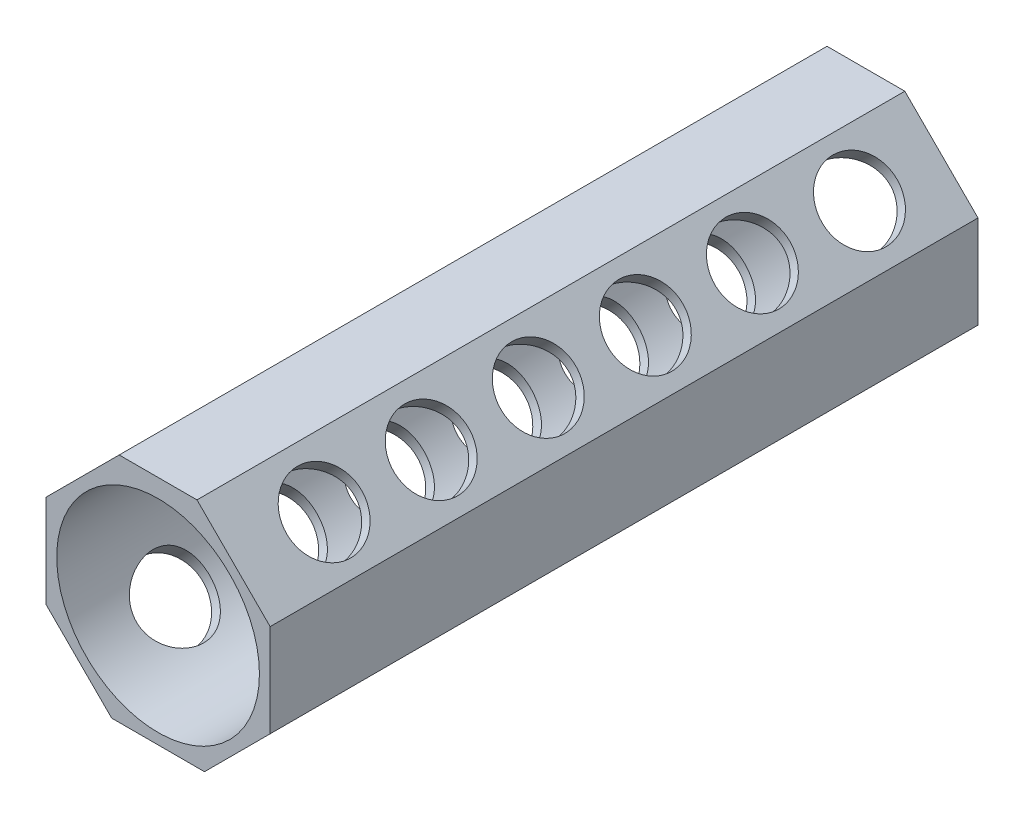
SolidWorks part; units mm, degrees
ref_plane "Ebene vorne" through (0, 0, 0) normal (1, 0, 0) x (0, 1, 0)
ref_plane "Ebene oben" through (0, 0, 0) normal (0, 0, 1) x (0, 1, 0)
ref_plane "Ebene rechts" through (0, 0, 0) normal (0, 1, 0) x (-1, 0, 0)
sketch "Skizze1" plane through (0, 0, 0) normal (0, 0, 1) x (0, 1, 0)
  line L0 (11.1508, 3.6277) -> (11.1508, -3.6277)
  line L13 (11.1508, 3.6277) -> (4.3285, 10.45)
  line L14 (4.3285, 10.45) -> (-4.3285, 10.45)
  line L15 (-4.3285, 10.45) -> (-10.45, 4.3285)
  line L16 (-10.45, 4.3285) -> (-10.45, -4.3285)
  line L17 (-10.45, -4.3285) -> (-4.3285, -10.45)
  line L18 (-4.3285, -10.45) -> (4.3285, -10.45)
  line L19 (4.3285, -10.45) -> (11.1508, -3.6277)
  line L29 (10.45, -2.605) -> (10.45, 5.6378) [skipped]
  circle A0 centre (0, 0) radius 9.45
  circle A1 centre (0, 0) radius 10.45 construction
  dimension "D1" = 18.9
  dimension "D2" = 20.9
extrude "Aufsatz-Linear austragen1" add sketch "Skizze1" along normal blind 66
sketch "Skizze9" plane through (7.3893, 7.3893, 0) normal (0.7071, 0.7071, 0) x (-0.7071, 0.7071, 0)
  line L0 (0.4955, 66) -> (0, 0) construction
  line L1 (-4.3285, 66) -> (5.3196, 66) construction
  circle A0 centre (0.4325, 57.6) radius 3.5
  circle A1 centre (0.4566, 47.6) radius 3.5
  circle A2 centre (0.4807, 37.6001) radius 3.5
  circle A3 centre (0.5048, 27.6001) radius 3.5
  circle A4 centre (0.5289, 17.6001) radius 3.5
  circle A5 centre (0.553, 7.6001) radius 3.5
  dimension "D1" = 7
  dimension "D2" = 8.4
  dimension "D3" = 6
extrude "Schnitt-Linear austragen8" cut sketch "Skizze9" against normal through all
sketch "Skizze10" plane through (0, 11.1508, 0) normal (0, 1, 0) x (-1, 0, 0)
  line L0 (0, 66) -> (0, 0) construction
  line L1 (-3.6277, 66) -> (3.6277, 66) construction
  line L2 (0, 8.4) -> (0, 57.6) construction
  line L3 (-3, 8.4) -> (-3, 57.6)
  line L4 (3, 8.4) -> (3, 57.6)
  arc A0 (-3, 8.4) -> (3, 8.4) centre (0, 8.4) ccw
  arc A1 (3, 57.6) -> (-3, 57.6) centre (0, 57.6) ccw
  point P7 (0, 33)
  dimension "D2" = 3
  dimension "D1" = 8.4
sketch "Skizze11" plane through (10.45, 0, 0) normal (1, 0, 0) x (0, 1, 0)
  line L0 (0, 66) -> (0, 0) construction
  line L1 (-4.3285, 66) -> (4.3285, 66) construction
  line L2 (0, 8.4) -> (0, 57.6) construction
  line L3 (-3, 8.4) -> (-3, 57.6)
  line L4 (3, 8.4) -> (3, 57.6)
  arc A0 (-3, 8.4) -> (3, 8.4) centre (0, 8.4) ccw
  arc A1 (3, 57.6) -> (-3, 57.6) centre (0, 57.6) ccw
  point P7 (0, 33)
  dimension "D1" = 3
  dimension "D2" = 8.4
